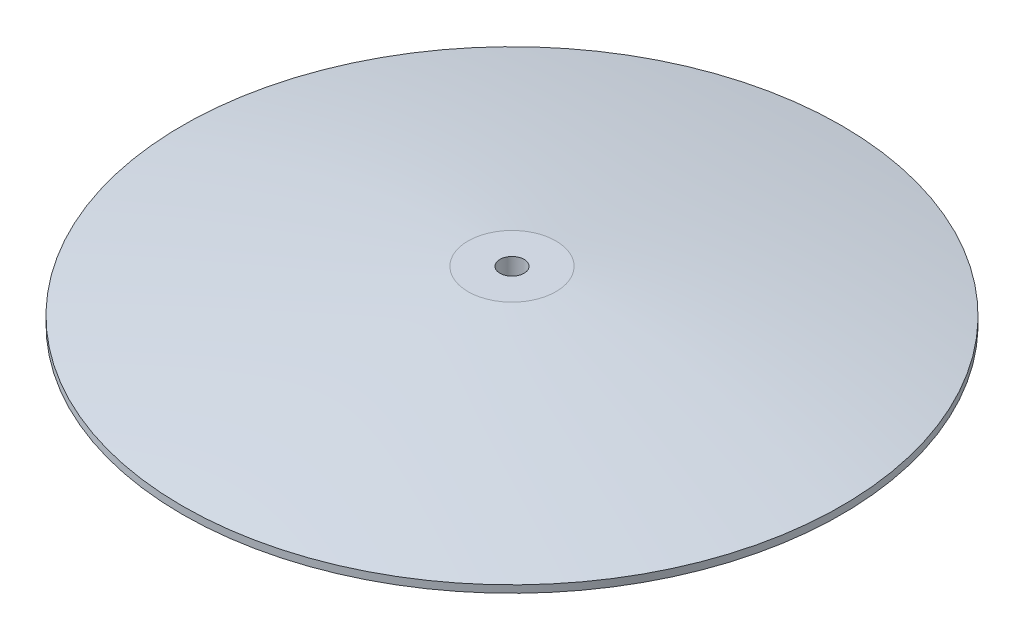
SolidWorks part; units mm, degrees
ref_plane "前视基准面" through (0, 0, 0) normal (0, 0, 1) x (1, 0, 0)
ref_plane "上视基准面" through (0, 0, 0) normal (0, 1, 0) x (1, 0, 0)
ref_plane "右视基准面" through (0, 0, 0) normal (1, 0, 0) x (0, 0, -1)
sketch "草图2" plane through (0, 0, 0) normal (0, 0, 1) x (1, 0, 0)
  line L0 (0, 0) -> (45, 0) construction
  line L1 (45, 0) -> (45, 1)
  line L2 (45, 1) -> (0, 7.3243) construction
  line L3 (0, 7.3243) -> (0, 0) construction
  line L4 (0, 7.3243) -> (0, 3.8243)
  line L5 (0, 6.8484) -> (6, 6.8484)
  spline S0 degree 2 poles (0, 3.8243) (22.6631, 4.0459) (45, 0) knots 0 0 0 1 1 1
  spline S1 degree 2 poles (0, 7.3243) (22.7183, 5.7323) (45, 1) knots 0 0 0 1 1 1
  dimension "D1" = 45
  dimension "D2" = 1
  dimension "D3" = 8
  dimension "D4" = 3.5
  dimension "D5" = 6
revolve "旋转1" add sketch "草图2" angle 360 about L3
sketch "草图3" plane through (0, 6.8484, 0) normal (0, 1, 0) x (1, 0, 0)
  circle A0 centre (0, 0) radius 1.65
  dimension "D1" = 3.3
extrude "切除-拉伸1" cut sketch "草图3" against normal blind 10
